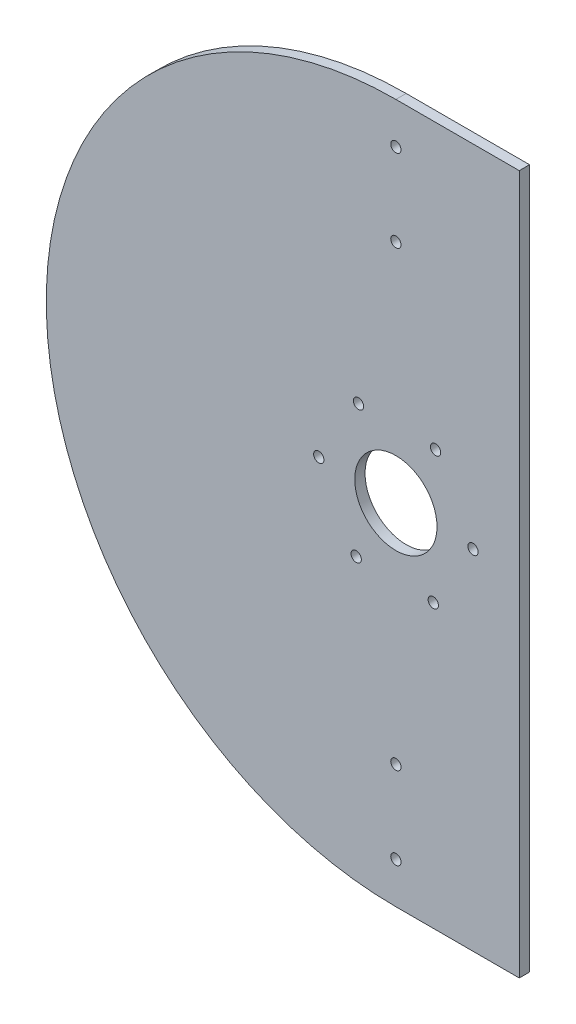
SolidWorks part; units mm, degrees
ref_plane "Front Plane" through (0, 0, 0) normal (0, 0, 1) x (1, 0, 0)
ref_plane "Top Plane" through (0, 0, 0) normal (0, 1, 0) x (1, 0, 0)
ref_plane "Right Plane" through (0, 0, 0) normal (1, 0, 0) x (0, 0, -1)
sketch "Sketch1" plane through (0, 0, 0) normal (0, 0, 1) x (1, 0, 0)
  line L0 (0, 107.95) -> (0, -107.95) construction
  line L1 (0, 107.95) -> (38.1, 107.95)
  line L2 (38.1, 107.95) -> (38.1, -107.95)
  line L3 (38.1, -107.95) -> (0, -107.95)
  arc A1 (0, 107.95) -> (0, -107.95) centre (0, 0) ccw
  dimension "D1" = 215.9
  dimension "D2" = 38.1
extrude "Boss-Extrude1" add sketch "Sketch1" along normal blind 3.175
hole_wizard "1/8 (0.125) Diameter Hole1" positions "Sketch4" profile "Sketch5" hole size "1/8" standard "ANSI Inch" end condition through all
sketch "Sketch4" plane through (0, 0, 0) normal (0, 0, -1) x (-1, 0, 0)
  line L0 (0, 107.95) -> (0, -107.95) construction
  line L2 (23.8089, 0.4135) -> (11.5464, 20.8259)
  line L3 (11.5464, 20.8259) -> (-12.2625, 20.4124)
  line L4 (-12.2625, 20.4124) -> (-23.8089, -0.4135)
  line L5 (-23.8089, -0.4135) -> (-11.5464, -20.8259)
  line L6 (-11.5464, -20.8259) -> (12.2625, -20.4124)
  line L7 (12.2625, -20.4124) -> (23.8089, 0.4135)
  circle A1 centre (0, 0) radius 20.6222 construction
  point P8 (0, 95.25)
  point P10 (0, -95.25)
  point P13 (0, -69.85)
  point P15 (0, 69.85)
  point P18 (0, 0)
  point P25 (23.8089, 0.4135)
  point P26 (11.5464, 20.8259)
  point P27 (-12.2625, 20.4124)
  point P28 (-23.8089, -0.4135)
  point P29 (-11.5464, -20.8259)
  point P30 (12.2625, -20.4124)
  point P57 (0, 0)
  point P58 (0, 0)
  dimension "D1" = 12.7
  dimension "D2" = 12.7
  dimension "D3" = 25.4
  dimension "D4" = 25.4
  dimension "D5" = 23.8125
sketch "Sketch5" plane through (-12.2625, -20.4124, 0) normal (1, 0, 0) x (0, 1, 0)
  line L0 (0, 0) -> (0, 3.175)
  line L1 (0, 3.175) -> (1.5875, 3.175)
  line L2 (1.5875, 3.175) -> (1.5875, 0)
  line L5 (1.5875, 0) -> (0, 0)
  line L11 (0, -6.35) -> (0, 107.95) construction
  dimension "Thru Hole Dia." = 3.175
  dimension "Thru Hole Depth" = 3.175
sketch "Sketch6" plane through (0, 0, 0) normal (0, 0, -1) x (-1, 0, 0)
  circle A0 centre (0, 0) radius 12.7
  dimension "D1" = 25.4
extrude "Cut-Extrude1" cut sketch "Sketch6" against normal blind 17.0815
